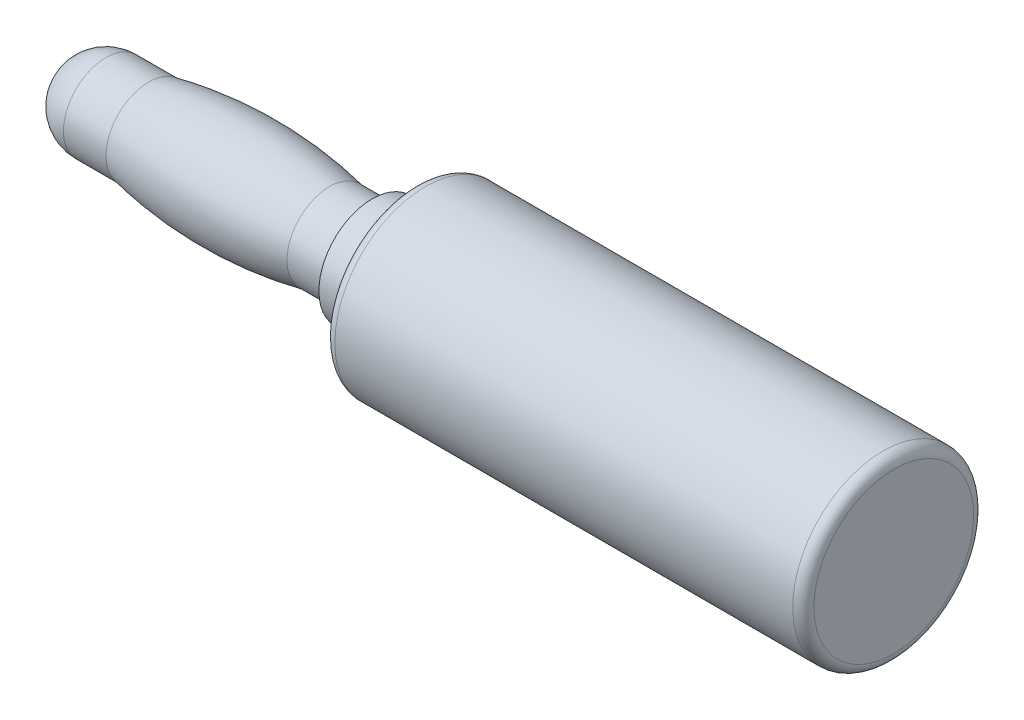
SolidWorks part; units mm, degrees
ref_plane "Front Plane" through (0, 0, 0) normal (0, 0, 1) x (1, 0, 0)
ref_plane "Top Plane" through (0, 0, 0) normal (0, 1, 0) x (1, 0, 0)
ref_plane "Right Plane" through (0, 0, 0) normal (1, 0, 0) x (0, 0, -1)
sketch "Sketch1" plane through (0, 0, 0) normal (0, 0, 1) x (1, 0, 0)
  line L0 (0, 0) -> (-39, 0)
  line L1 (0, 0) -> (0, 4.25)
  line L2 (0, 4.25) -> (-22.5, 4.25)
  line L3 (-22.5, 4.25) -> (-22.5, 2.5)
  line L4 (-22.5, 2.5) -> (-24.5, 2.5)
  line L5 (-24.5, 2.5) -> (-24.5, 2)
  line L6 (-24.5, 2) -> (-26.5, 2)
  line L7 (-26.5, 2) -> (-35, 2) construction
  line L8 (-35, 2) -> (-37, 2)
  line L9 (-39, 0) -> (-43.5036, 0) construction
  arc A0 (-37, 2) -> (-39, 0) centre (-37, 0) ccw
  arc A2 (-35, 2) -> (-26.5, 2) centre (-30.75, -18.6577) cw
  dimension "D1" = 39
  dimension "D2" = 4.25
  dimension "D3" = 22.5
  dimension "D4" = 2
  dimension "D5" = 2.5
  dimension "D6" = 2
  dimension "D7" = 2
  dimension "D8" = 2
  dimension "D9" = 2
revolve "Revolve1" add sketch "Sketch1" angle 360 about L9
chamfer "Chamfer1" distance 0.5 angle 45 1 edges at (-22.5, 2.5, 0)
fillet "Fillet1" radius 0.5 2 edges at (0, 4.25, 0) (-22.5, 4.25, 0)
sketch "Sketch3" plane through (0, 0, 0) normal (0, 1, 0) x (1, 0, 0)
  line L0 (0, 0) -> (-19.05, 0) construction
  circle A0 centre (-19.05, 0) radius 2
  circle A1 centre (-12.7, 0) radius 2
  dimension "D1" = 4
  dimension "D3" = 4
  dimension "D2" = 19.05
  dimension "D4" = 6.35
extrude "Cut-Extrude1" cut sketch "Sketch3" against normal blind 25.4
